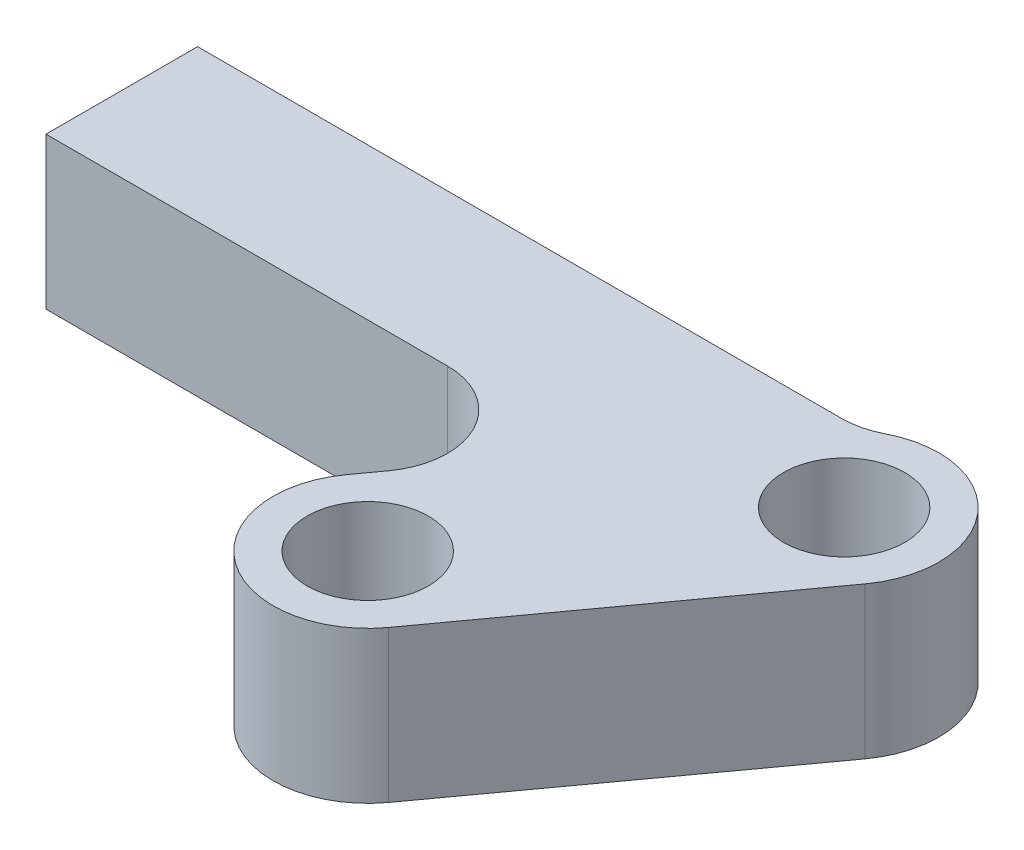
SolidWorks part; units mm, degrees
ref_plane "正面" through (0, 0, 0) normal (0, 0, 1) x (1, 0, 0)
ref_plane "平面" through (0, 0, 0) normal (0, 1, 0) x (1, 0, 0)
ref_plane "右側面" through (0, 0, 0) normal (1, 0, 0) x (0, 0, -1)
sketch "ｽｹｯﾁ2" plane through (0, 0, 0) normal (0, 1, 0) x (1, 0, 0)
  line L0 (2.0225, -1.4695) -> (-3.2675, -8.7506)
  line L1 (-6.8504, -5.1756) -> (-7.3126, -5.8117)
  line L2 (-19.0616, -2) -> (-8.4685, -2)
  line L3 (-19.0616, -2) -> (-19.0616, 2)
  line L4 (-19.0616, 2) -> (-2.0616, 2)
  circle A0 centre (0, 0) radius 1.6
  circle A1 centre (-5.2901, -7.2812) radius 1.6
  arc A2 (2.0225, -1.4695) -> (-1.1453, 2.2222) centre (0, 0) ccw
  arc A3 (-7.3126, -5.8117) -> (-3.2675, -8.7506) centre (-5.2901, -7.2812) ccw
  arc A4 (-8.4685, -2) -> (-6.8504, -5.1756) centre (-8.4685, -4) cw
  arc A5 (-2.0616, 2) -> (-1.1453, 2.2222) centre (-2.0616, 4) ccw
  point P8 (0.7265, -5.7367)
  point P14 (0.1962, -0.7549)
  point P15 (0, -0.7515)
  point P18 (0, 0)
  point P20 (-19.0616, 0)
  point P21 (-4.0573, -8.0336)
  dimension "D1" = 3.2
  dimension "D2" = 5
  dimension "D3" = 2
  dimension "D4" = 2
  dimension "D5" = 9
  dimension "D6" = 4
  dimension "D7" = 54
  dimension "D8" = 17
extrude "ﾎﾞｽ - 押し出し1" add sketch "ｽｹｯﾁ2" along normal blind 4
